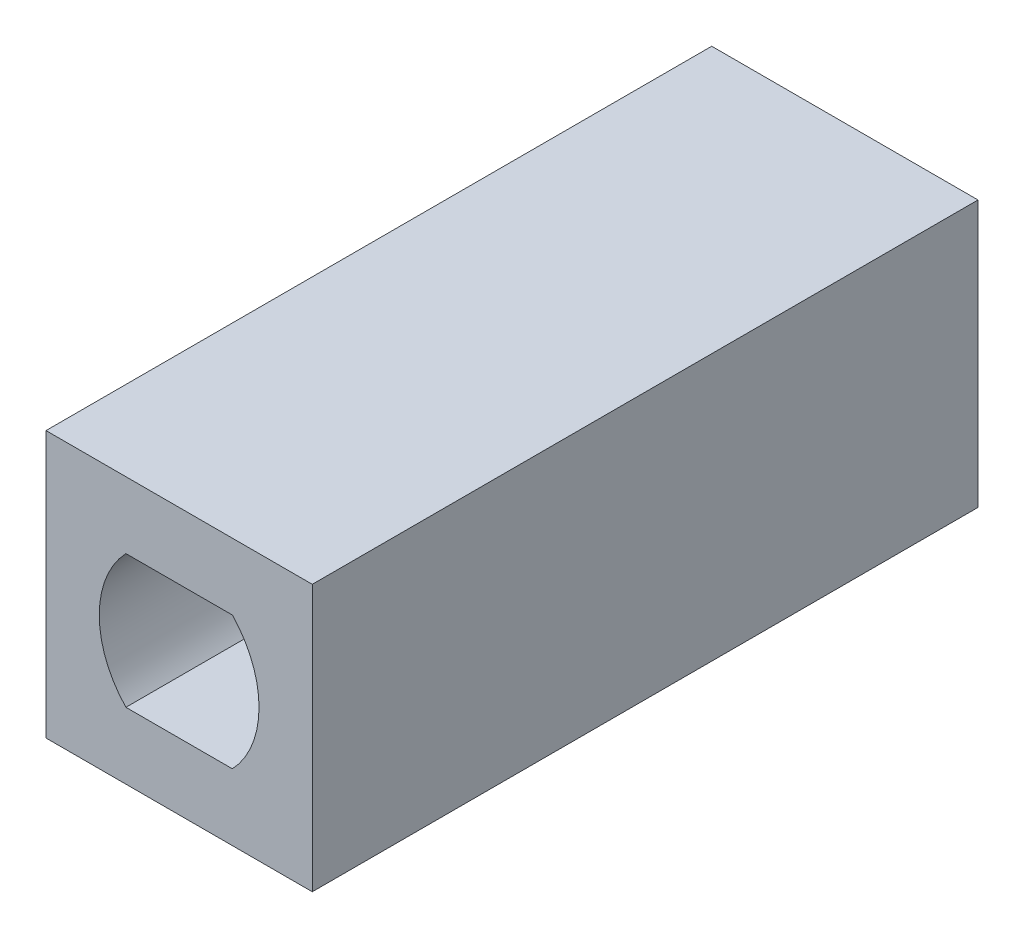
SolidWorks part; units mm, degrees
ref_plane "前基準面" through (0, 0, 0) normal (0, 0, 1) x (1, 0, 0)
ref_plane "上基準面" through (0, 0, 0) normal (0, 1, 0) x (1, 0, 0)
ref_plane "右基準面" through (0, 0, 0) normal (1, 0, 0) x (0, 0, -1)
sketch "草圖1" plane through (0, 0, 0) normal (0, 0, 1) x (1, 0, 0)
  line L1 (-10, -10) -> (10, -10)
  line L2 (-10, -10) -> (-10, 10)
  line L3 (-10, 10) -> (10, 10)
  line L4 (10, -10) -> (10, 10)
  line L5 (-10, -10) -> (10, 10) construction
  line L6 (-10, 10) -> (10, -10) construction
  point P0 (0, 0)
  dimension "D1" = 20
  dimension "D2" = 20
extrude "填料-伸長1" add sketch "草圖1" along normal blind 50
sketch "草圖2" plane through (0, 0, 0) normal (0, 0, 1) x (1, 0, 0)
  line L0 (-4, 5) -> (4, 5)
  line L1 (-1000, 0) -> (49000, 0) construction
  line L2 (-4, -5) -> (4, -5)
  line L3 (0, -1000) -> (0, 49000) construction
  arc A0 (-4, 5) -> (-4, -5) centre (1.25, 0) ccw
  arc A1 (4, 5) -> (4, -5) centre (-1.25, 0) cw
  point P11 (-6, 0)
  point P12 (6, 0)
  point P13 (2.4832, 5.2052)
  dimension "D2" = 12
  dimension "D1" = 10
  dimension "D3" = 8
extrude "除料-伸長1" cut sketch "草圖2" along normal blind 50
